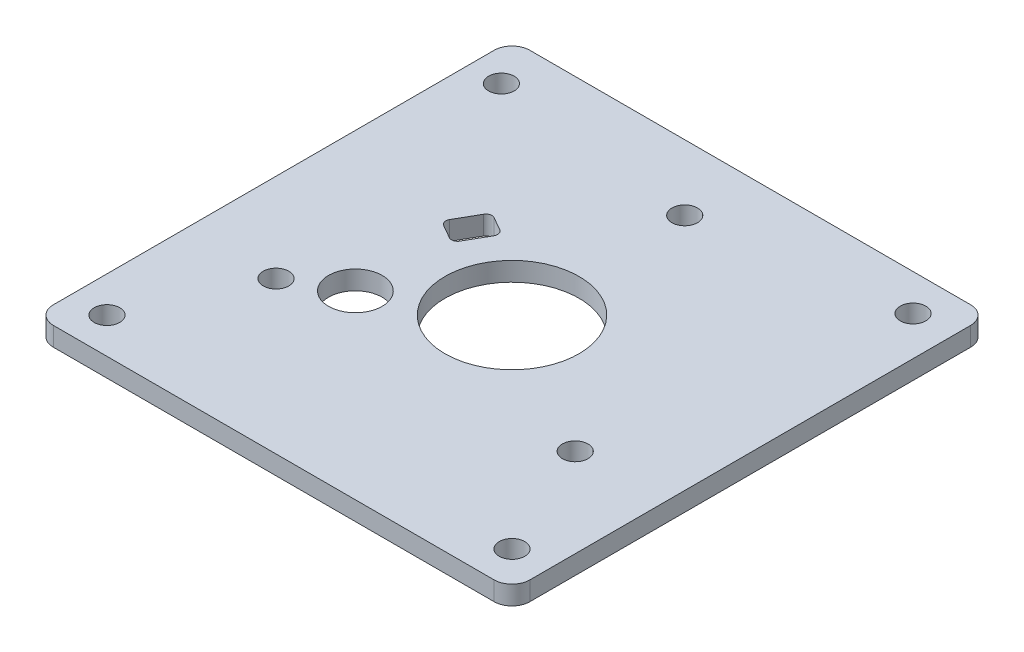
SolidWorks part; units mm, degrees
ref_plane "Front Plane" through (0, 0, 0) normal (0, 0, 1) x (1, 0, 0)
ref_plane "Top Plane" through (0, 0, 0) normal (0, 1, 0) x (1, 0, 0)
ref_plane "Right Plane" through (0, 0, 0) normal (1, 0, 0) x (0, 0, -1)
sketch "Sketch1" plane through (0, 0, 0) normal (0, 1, 0) x (1, 0, 0)
  line L0 (0, 40) -> (0, -39.3152) construction
  line L1 (-40, -40) -> (40, -40)
  line L2 (-40, -40) -> (-40, 40)
  line L3 (-40, 40) -> (40, 40)
  line L4 (40, -40) -> (40, 40)
  line L5 (-40, -40) -> (40, 40) construction
  line L6 (-40, 40) -> (40, -40) construction
  line L7 (-40, -0.6614) -> (40, 0) construction
  line L8 (-25.1147, -14.5) -> (0, 0) construction
  line L9 (-19.6262, 7.7818) -> (-15.6351, 5.4947)
  line L10 (-15.6351, 5.4947) -> (-12.5525, 10.8741)
  line L11 (-12.5525, 10.8741) -> (-16.5436, 13.1612)
  line L12 (-16.5436, 13.1612) -> (-19.6262, 7.7818)
  circle A0 centre (0, 0) radius 11.25
  circle A1 centre (0, 29) radius 2.15
  circle A2 centre (25.1147, -14.5) radius 2.15
  circle A3 centre (-25.1147, -14.5) radius 2.15
  circle A4 centre (-34, -34) radius 2.15
  circle A5 centre (34, -34) radius 2.15
  circle A6 centre (33.4387, 33.8961) radius 2.15
  circle A7 centre (-34.552, 32.7718) radius 2.15
  circle A8 centre (-16.671, -9.625) radius 4.5
  point P0 (0, 0)
  point P16 (0, 0)
  point P29 (-13.6278, 9.2371)
  point P34 (-20.7046, 10.8842)
  point P35 (-16.9945, 6.7312)
  point P36 (-21.4514, 9.0154)
  point P37 (-12.75, 11.1906)
  point P38 (-12.7707, 11.0864)
  point P39 (-16.5436, 13.1612)
  dimension "D1" = 22.5
  dimension "D2" = 4.3
  dimension "D7" = 4.3
  dimension "D10" = 9
  dimension "D3" = 29
  dimension "D5" = 80
  dimension "D6" = 80
  dimension "D8" = 6
  dimension "D9" = 6
  dimension "D11" = 19.25
  dimension "D12" = 0
  dimension "D13" = 4.6
  dimension "D14" = 6.2
  dimension "D15" = 90
  dimension "D4" = 3
extrude "Boss-Extrude1" add sketch "Sketch1" along normal blind 3.175
fillet "Fillet1" radius 3 4 edges at (-40, 1.5875, 40) (40, 1.5875, 40) (40, 1.5875, -40) (-40, 1.5875, -40)
fillet "Fillet2" radius 1 4 edges at (-19.6262, 1.5875, -7.7818) (-15.6351, 1.5875, -5.4947) (-12.5525, 1.5875, -10.8741) (-16.5436, 1.5875, -13.1612)
